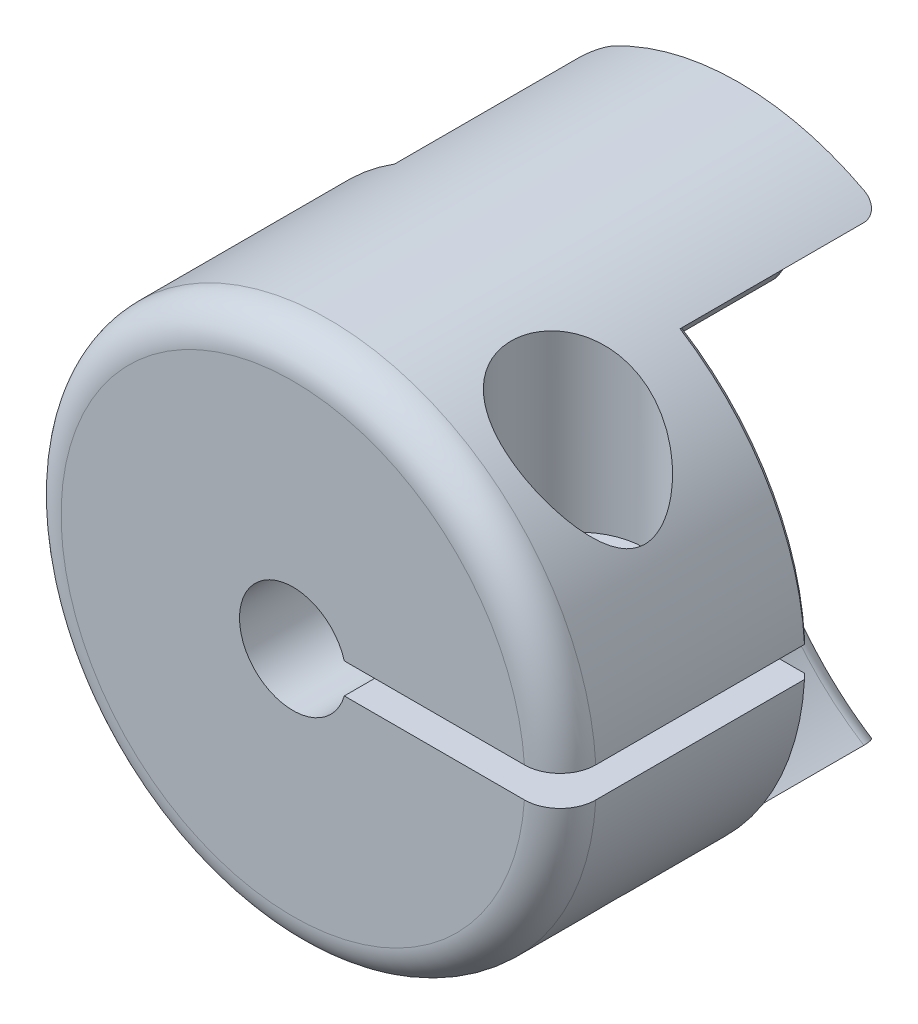
SolidWorks part; units mm, degrees
material "1060 Alloy"
ref_plane "Front Plane" through (0, 0, 0) normal (0, 0, 1) x (1, 0, 0)
ref_plane "Top Plane" through (0, 0, 0) normal (0, 1, 0) x (1, 0, 0)
ref_plane "Right Plane" through (0, 0, 0) normal (1, 0, 0) x (0, 0, -1)
sketch "Sketch1" plane through (0, 0, 0) normal (0, 0, 1) x (1, 0, 0)
  circle A0 centre (0, 0) radius 15
  circle A1 centre (0, 0) radius 3
  dimension "D1" = 30
extrude "Boss-Extrude1" add sketch "Sketch1" along normal mid plane 25
sketch "Sketch2" plane through (0, 0, -12.5) normal (0, 0, -1) x (-1, 0, 0)
  line L0 (0, 0) -> (-16, 0) construction
  line L1 (0, 30.9567) -> (0, 22.4384) construction
  circle A0 centre (-16, 0) radius 15
  circle A1 centre (16, 0) radius 15
  dimension "D2" = 30
  dimension "D1" = 16
extrude "Cut-Extrude1" cut sketch "Sketch2" against normal blind 11
sketch "Sketch3" plane through (0, 0, -12.5) normal (0, 0, -1) x (-1, 0, 0)
  line L0 (0, 0) -> (5.5, 0) construction
  line L1 (7.9547, -0.85) -> (11, -0.85)
  line L2 (0, -0.85) -> (0, 0.85) construction
  line L3 (7.9547, 0.85) -> (11, 0.85)
  line L4 (11, -0.85) -> (11, 0.85)
  line L5 (0, -0.85) -> (11, 0.85) construction
  line L6 (0, 0.85) -> (11, -0.85) construction
  arc A0 (7.9547, 0.85) -> (7.9547, -0.85) centre (0, 0) ccw
  point P3 (5.5, 0)
  dimension "D1" = 16
  dimension "D2" = 1.7
  dimension "D3" = 11
extrude "Cut-Extrude2" cut sketch "Sketch3" against normal blind 12
sketch "Sketch6" plane through (0, -0.85, 0) normal (0, 1, 0) x (1, 0, 0)
  line L0 (-11, 0.5) -> (15, -25.5)
  line L1 (-11, 0.5) -> (15, 0.5) construction
  line L2 (15, 0.5) -> (15, -25.5)
  line L3 (15, -12.5) -> (15, 1.5) construction
  line L4 (15, 0.5) -> (15, 1.5)
  line L5 (15, 1.5) -> (-11, 1.5)
  line L6 (-11, 1.5) -> (-11, 0.5)
  dimension "D1" = 45
extrude "Cut-Extrude3" cut sketch "Sketch6" along normal up to surface (1.7 mm away) up to face at (-9.4774, 0.85, -1)
sketch "Sketch7" plane through (0, 0, 0) normal (0, 1, 0) x (1, 0, 0)
  line L0 (-15, -12.5) -> (14.9759, -12.5) construction
  line L1 (14.9759, -12.5) -> (14.9759, 1.5) construction
  circle A0 centre (8.9759, -5.5) radius 2
  dimension "D1" = 4
  dimension "D2" = 7
  dimension "D3" = 6
extrude "Cut-Extrude4" cut sketch "Sketch7" against normal through all both and the other way through all
sketch "Sketch8" plane through (0, -0.85, 0) normal (0, 1, 0) x (1, 0, 0)
  circle A0 centre (8.9759, -5.5) radius 3.75
  dimension "D1" = 7.5
extrude "Cut-Extrude5" cut sketch "Sketch8" along normal through all from offset 4.85
fillet "Fillet1" radius 2 1 edges at (-15, 0, 12.5)
fillet "Fillet2" radius 1 6 edges at (0, 8, -12.5) (0, -8, -12.5) (5.1605, -10.3685, -12.5) (5.1605, 10.3685, -12.5) (-5.1605, 10.3685, -12.5) (-5.1605, -10.3685, -12.5)
chamfer "Chamfer1" distance 0.3 angle 45 3 edges at (12.9233, -7.6151, -1.5) (12.9233, 7.6151, -1.5) (-15, 0, -1.5)
equation "\"inner diameter\" = 6mm"
equation "\"D2@Sketch1\"=\"inner diameter\""
